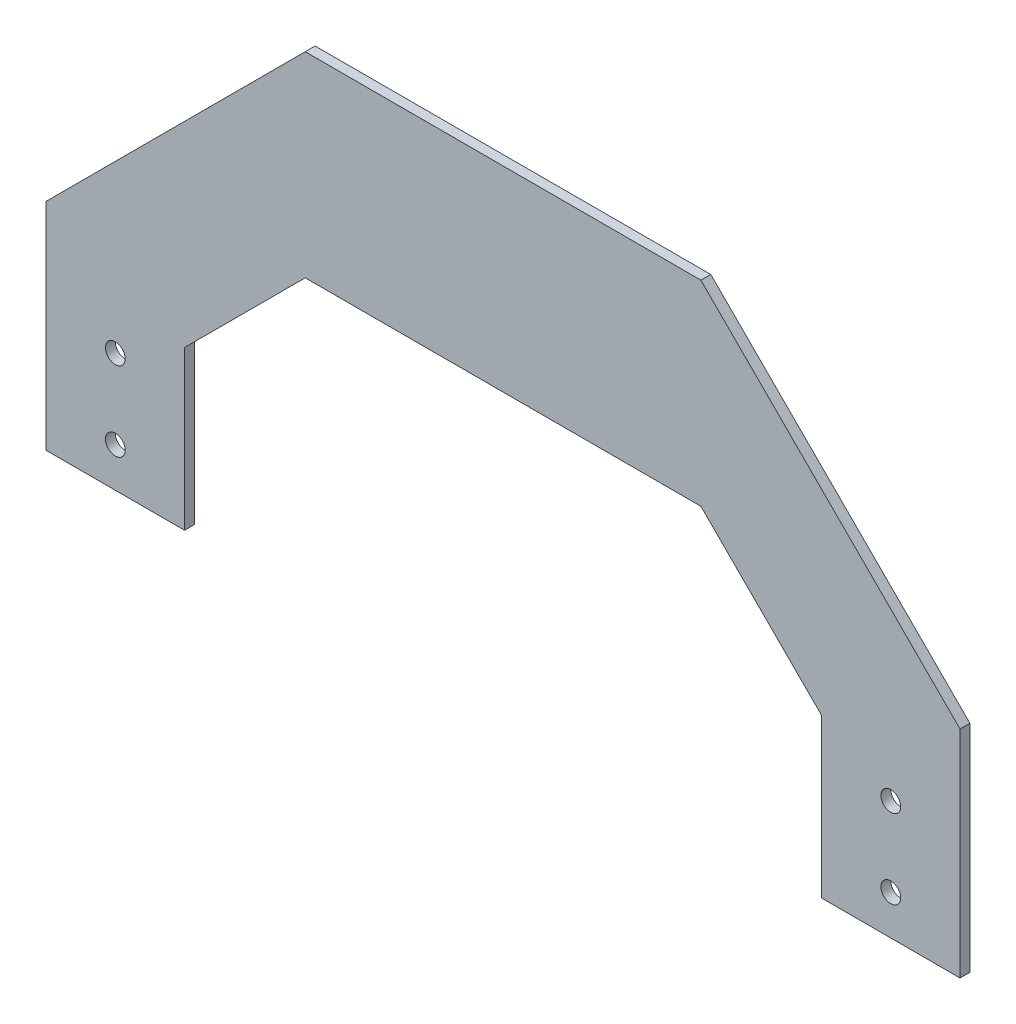
SolidWorks part; units mm, degrees
ref_plane "Front Plane" through (0, 0, 0) normal (0, 0, 1) x (1, 0, 0)
ref_plane "Top Plane" through (0, 0, 0) normal (0, 1, 0) x (1, 0, 0)
ref_plane "Right Plane" through (0, 0, 0) normal (1, 0, 0) x (0, 0, -1)
sketch "Sketch1" plane through (0, 0, 0) normal (0, 0, 1) x (1, 0, 0)
  line L0 (-63.5, 31.4309) -> (-146.6882, -51.7573)
  line L1 (-63.5, -31.4309) -> (0, -31.4309)
  line L2 (-63.5, -31.4309) -> (-63.5, 31.4309) construction
  line L3 (-63.5, 31.4309) -> (0, 31.4309)
  line L4 (0, 31.4309) -> (0, -31.4309)
  line L5 (-63.5, -31.4309) -> (0, 0) construction
  line L6 (-63.5, 31.4309) -> (0, 0) construction
  line L7 (-63.5, -31.4309) -> (-102.2382, -70.1691)
  line L11 (-146.6882, -51.7573) -> (-146.6882, -120.9691)
  line L12 (-102.2382, -70.1691) -> (0, -70.1691) construction
  line L13 (0, 31.4309) -> (0, -70.1691) construction
  line L14 (-146.6882, -120.9691) -> (-102.2382, -120.9691)
  line L15 (-102.2382, -70.1691) -> (-102.2382, -120.9691)
  point P0 (0, 0)
  dimension "D1" = 44.45
  dimension "D2" = 63.5
  dimension "D3" = 135
  dimension "D4" = 44.45
  dimension "D5" = 50.8
  dimension "D6" = 101.6
extrude "Boss-Extrude1" add sketch "Sketch1" along normal blind 3.175
sketch "Sketch4" plane through (0, 0, 3.175) normal (0, 0, 1) x (1, 0, 0)
  line L0 (-102.2382, -70.1691) -> (-146.6882, -70.1691) construction
  line L1 (-146.6882, -51.7573) -> (-146.6882, -120.9691) construction
  line L2 (-124.4632, -70.1691) -> (-124.4632, -120.9691) construction
  line L3 (-146.6882, -120.9691) -> (-102.2382, -120.9691) construction
  circle A0 centre (-124.4632, -108.2691) radius 3.175
  circle A1 centre (-124.4632, -82.8691) radius 3.175
  dimension "D1" = 6.35
  dimension "D2" = 6.35
  dimension "D3" = 12.7
  dimension "D4" = 25.4
extrude "Cut-Extrude2" cut sketch "Sketch4" against normal blind 3.175
mirror "Mirror4" about plane through (0, 31.4309, 3.175) normal (-1, 0, 0) of "Boss-Extrude1", "Cut-Extrude2"
sketch "Sketch5" plane through (0, 0, 0) normal (0, 0, -1) x (-1, 0, 0)
  line L0 (0, 31.4309) -> (0, -31.4309) construction
  line L1 (-63.5, 31.4309) -> (63.5, 31.4309) construction
  line L2 (63.5, -31.4309) -> (-63.5, -31.4309) construction
